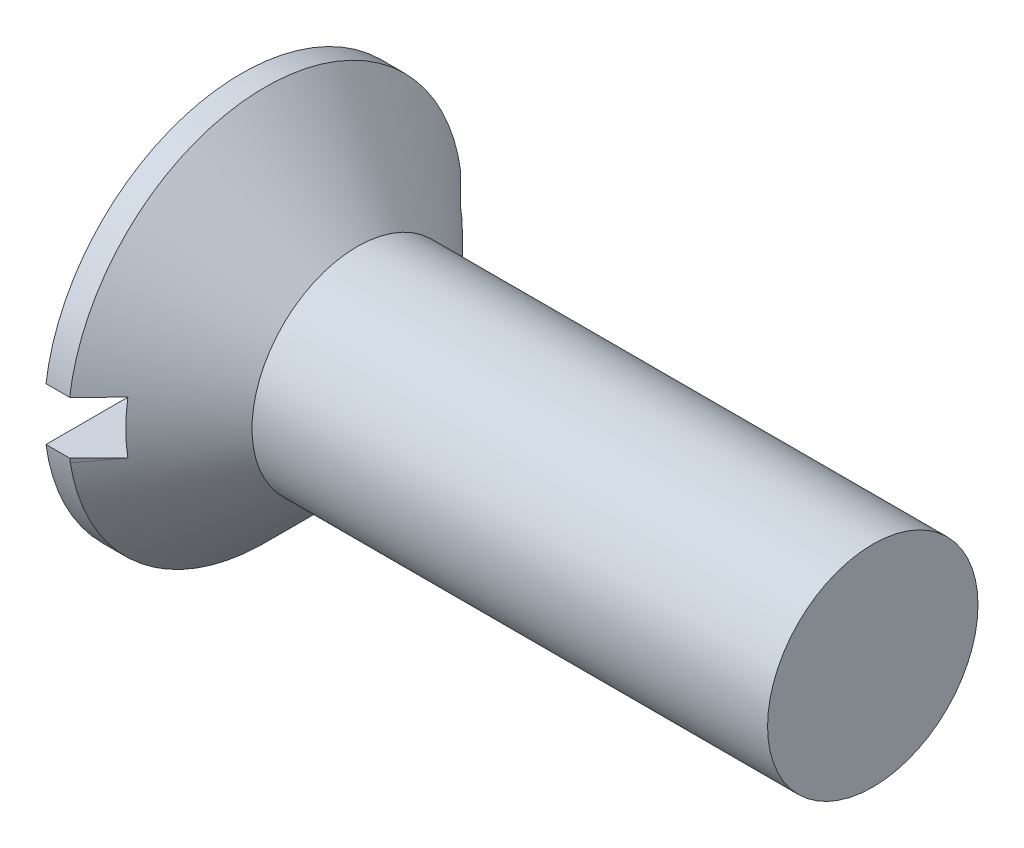
SolidWorks part; units mm, degrees
material "Plain Carbon Steel"
ref_plane "Front Plane" through (0, 0, 0) normal (0, 0, 1) x (1, 0, 0)
ref_plane "Top Plane" through (0, 0, 0) normal (0, 1, 0) x (1, 0, 0)
ref_plane "Right Plane" through (0, 0, 0) normal (1, 0, 0) x (0, 0, -1)
sketch "Sketch1" plane through (0, 0, 0) normal (0, 0, 1) x (1, 0, 0)
  line L0 (0, 0) -> (0, 3.75)
  line L1 (0, 3.75) -> (0.45, 3.75)
  line L2 (0.45, 3.75) -> (2.2, 2)
  line L3 (2.2, 2) -> (12, 2)
  line L4 (12, 2) -> (12, 0)
  line L5 (12, 0) -> (0, 0) construction
  line L6 (0, 0) -> (12, 0)
  dimension "D1" = 45
  dimension "D2" = 4
  dimension "D3" = 7.5
  dimension "D4" = 2.2
  dimension "D5" = 12
revolve "Revolve1" add sketch "Sketch1" angle 360 about L5
sketch "Sketch2" plane through (0, 0, 0) normal (-1, 0, 0) x (0, 0, 1)
  line L0 (3.75, 0) -> (-3.75, 0) construction
  line L1 (-3.75, 0.5) -> (3.75, 0.5)
  line L2 (-3.75, 0.5) -> (-3.75, -0.5)
  line L3 (-3.75, -0.5) -> (3.75, -0.5)
  line L4 (3.75, 0.5) -> (3.75, -0.5)
  circle A0 centre (0, 0) radius 3.75 construction
  dimension "D1" = 1
extrude "Cut-Extrude1" cut sketch "Sketch2" against normal blind 1
